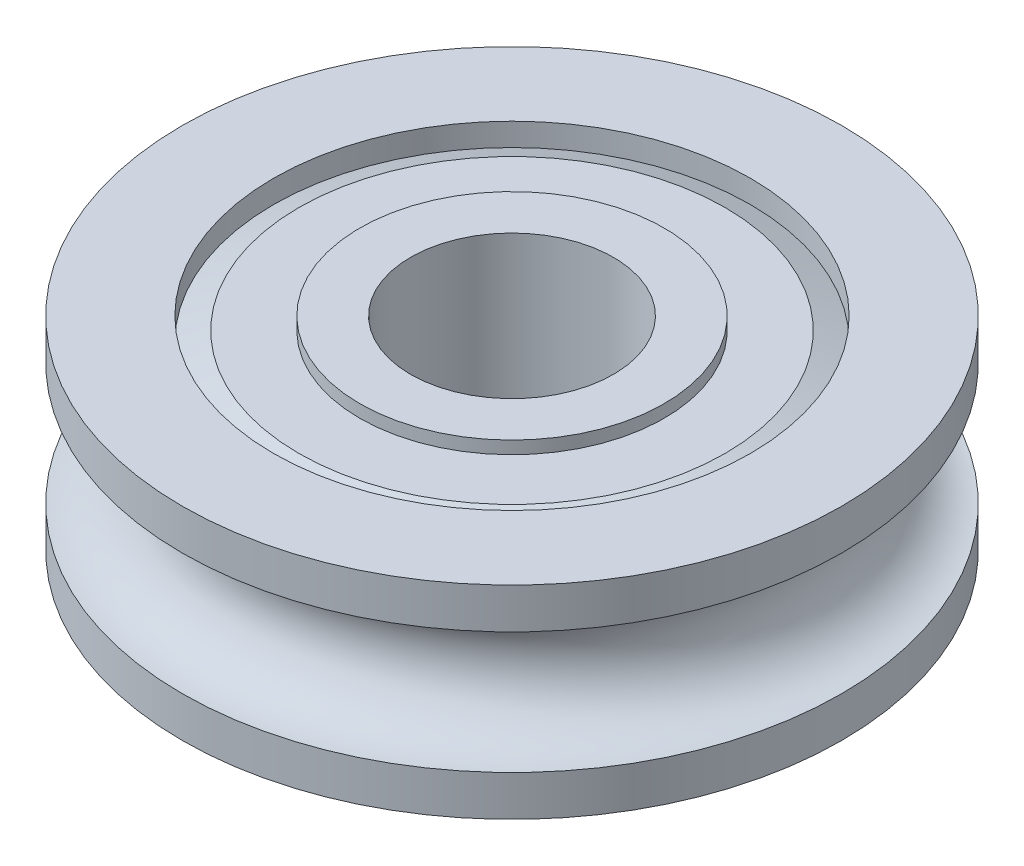
SolidWorks part; units mm, degrees
ref_plane "Front Plane" through (0, 0, 0) normal (0, 0, 1) x (1, 0, 0)
ref_plane "Top Plane" through (0, 0, 0) normal (0, 1, 0) x (1, 0, 0)
ref_plane "Right Plane" through (0, 0, 0) normal (1, 0, 0) x (0, 0, -1)
sketch "Sketch1" plane through (0, 0, 0) normal (0, 0, 1) x (1, 0, 0)
  line L0 (0, 2) -> (0, -2)
  line L1 (0, 2) -> (6.5, 2)
  line L2 (6.5, 2) -> (6.5, 1.2)
  line L3 (6.5, -1.2) -> (6.5, -2)
  line L4 (6.5, -2) -> (0, -2)
  arc A0 (6.5, 1.2) -> (6.5, -1.2) centre (6.5, 0) ccw
  point P4 (0, 0)
  dimension "D2" = 1.2
  dimension "D1" = 4
  dimension "D3" = 6.5
revolve "Revolve1" add sketch "Sketch1" angle 360 about L0
sketch "Sketch2" plane through (0, 2, 0) normal (0, 1, 0) x (1, 0, 0)
  circle A0 centre (0, 0) radius 2
  dimension "D1" = 4
extrude "Cut-Extrude1" cut sketch "Sketch2" against normal through all
sketch "Sketch3" plane through (0, 2, 0) normal (0, 1, 0) x (1, 0, 0)
  circle A0 centre (0, 0) radius 3
  circle A2 centre (0, 0) radius 4.7
  dimension "D1" = 9.4
  dimension "D2" = 6
extrude "Cut-Extrude2" cut sketch "Sketch3" against normal blind 0.25
sketch "Sketch4" plane through (0, 0, 0) normal (0, 0, 1) x (1, 0, 0)
  line L0 (4.7, 1.75) -> (4.2, 1.75)
  line L1 (4.7, 1.75) -> (-4.7, 1.75) construction
  line L2 (4.2, 1.75) -> (4.7, 1.55)
  line L3 (4.7, 1.55) -> (4.7, 1.75)
  dimension "D1" = 0.5
  dimension "D2" = 0.2
revolve "Cut-Revolve1" cut sketch "Sketch4" angle 360
mirror "Mirror1" about plane through (0, 0, 0) normal (0, 1, 0) of "Cut-Revolve1", "Cut-Extrude2"
